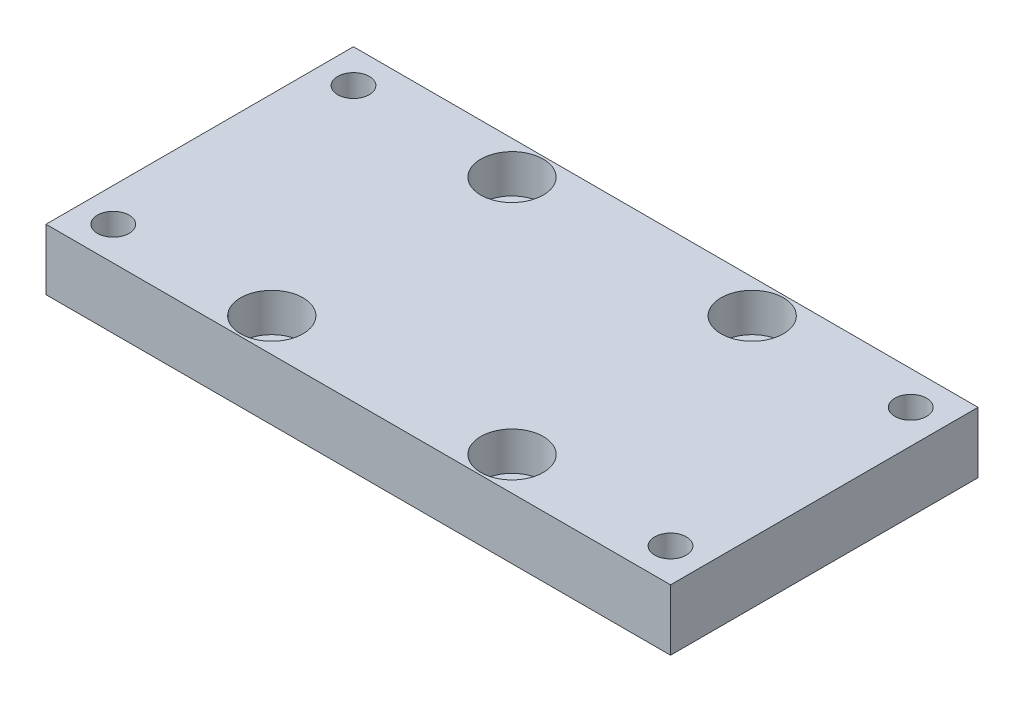
SolidWorks part; units mm, degrees
ref_plane "Front Plane" through (0, 0, 0) normal (0, 0, 1) x (1, 0, 0)
ref_plane "Top Plane" through (0, 0, 0) normal (0, 1, 0) x (1, 0, 0)
ref_plane "Right Plane" through (0, 0, 0) normal (1, 0, 0) x (0, 0, -1)
sketch "Sketch1" plane through (0, 0, 0) normal (0, 1, 0) x (1, 0, 0)
  line L1 (-32.5, -16) -> (32.5, -16)
  line L2 (-32.5, -16) -> (-32.5, 16)
  line L3 (-32.5, 16) -> (32.5, 16)
  line L4 (32.5, -16) -> (32.5, 16)
  line L5 (-32.5, -16) -> (32.5, 16) construction
  line L6 (-32.5, 16) -> (32.5, -16) construction
  point P0 (0, 0)
  dimension "D1" = 65
  dimension "D2" = 32
extrude "Extrude1" add sketch "Sketch1" along normal blind 6.35
sketch "Sketch3" plane through (0, 6.35, 0) normal (0, 1, 0) x (-1, 0, 0)
  line L0 (0, -24.9352) -> (0, 26.0817) construction
  line L1 (37.4888, 0) -> (-41.0428, 0) construction
hole_wizard "CBORE for M3 SHCS2" positions "3DSketch2" profile "Sketch4" counterbore size "M3" standard "Ansi Metric" end condition through all
sketch3d "3DSketch2"
  line L0 (-37.4888, 6.35, 0) -> (41.0428, 6.35, 0) construction
  line L1 (0, 6.35, -24.9352) -> (0, 6.35, 26.0817) construction
  point P0 (-12.5, 6.35, -12.5)
  dimension "D1" = 12.5
  dimension "D2" = 12.5
sketch "Sketch4" plane through (-12.5, 6.35, -12.5) normal (1, 0, 0) x (0, 0, 1)
  line L0 (0, 0) -> (0, 6.35)
  line L1 (0, 6.35) -> (1.7, 6.35)
  line L3 (1.7, 6.35) -> (1.7, 4)
  line L4 (1.7, 4) -> (3.25, 4)
  line L5 (3.25, 4) -> (3.25, 0)
  line L7 (3.25, 0) -> (0, 0)
  line L11 (0, -6.35) -> (0, 107.95) construction
  dimension "Thru Hole Dia." = 3.4
  dimension "Thru Hole Depth" = 6.35
  dimension "C'Bore Dia." = 6.5
  dimension "C'Bore Depth" = 4
pattern_linear "LPattern1" count 2 spacing 25 along (1, 0, 0) count 2 spacing 25 along (0, 0, 1) of "CBORE for M3 SHCS2"
hole_wizard "M4x0.7 Tapped Hole1" positions "3DSketch3" profile "Sketch5" tap size "M4x0.7" standard "Ansi Metric"
sketch3d "3DSketch3"
  line L0 (-37.4888, 6.35, 0) -> (41.0428, 6.35, 0) construction
  line L1 (0, 6.35, -24.9352) -> (0, 6.35, 26.0817) construction
  point P0 (-29, 6.35, -12.5)
  dimension "D1" = 12.5
  dimension "D2" = 29
sketch "Sketch5" plane through (-29, 6.35, -12.5) normal (1, 0, 0) x (0, 0, 1)
  line L0 (0, 0) -> (0, 12.4914)
  line L1 (0, 12.4914) -> (1.65, 11.5)
  line L2 (1.65, 11.5) -> (1.65, 0)
  line L5 (1.65, 0) -> (0, 0)
  line L10 (0, 12.4914) -> (-1.65, 11.5) construction
  line L11 (0, -6.35) -> (0, 107.95) construction
  dimension "Tap Drill Dia." = 3.3
  dimension "Tap Drill Depth" = 11.5
  dimension "Drill Angle" = 118
pattern_linear "LPattern2" count 2 spacing 58 along (1, 0, 0) count 2 spacing 25 along (0, 0, 1) of "M4x0.7 Tapped Hole1"
